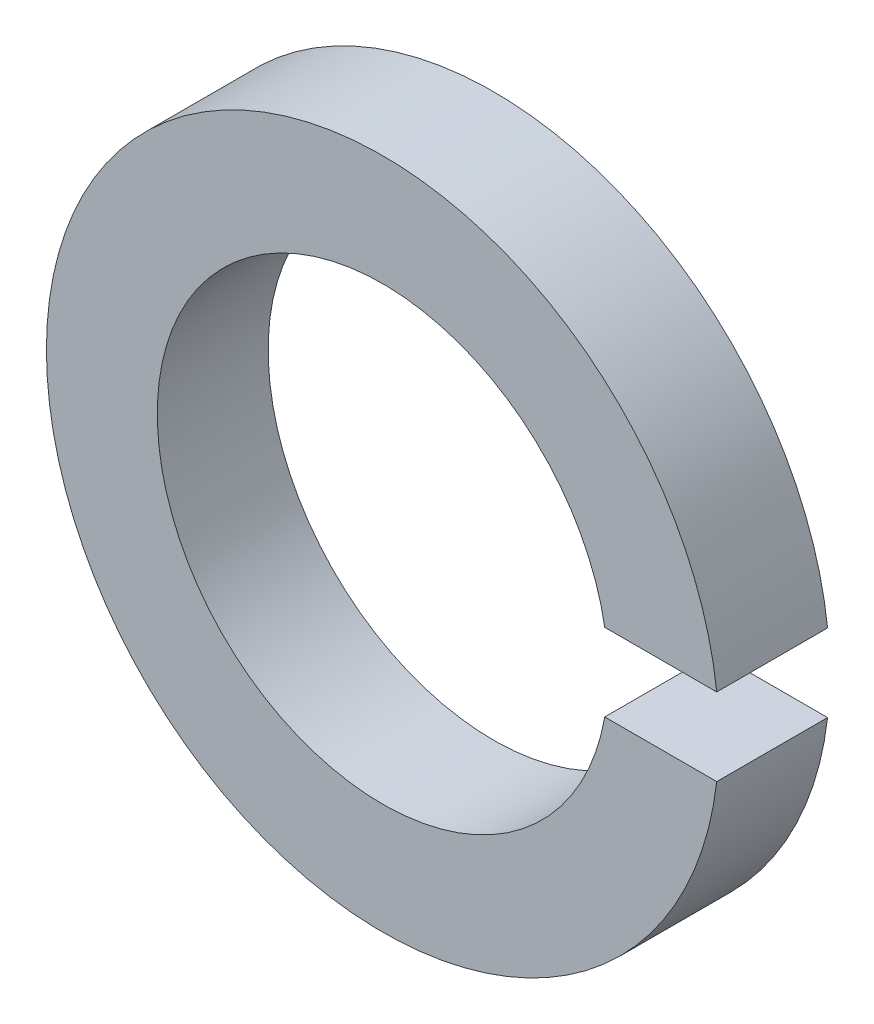
SolidWorks part; units mm, degrees
ref_plane "Спереди" through (0, 0, 0) normal (0, 0, 1) x (1, 0, 0)
ref_plane "Сверху" through (0, 0, 0) normal (0, 1, 0) x (1, 0, 0)
ref_plane "Справа" through (0, 0, 0) normal (1, 0, 0) x (0, 0, -1)
sketch "Эскиз1" plane through (0, 0, 0) normal (0, 0, 1) x (1, 0, 0)
  circle A0 centre (0, 0) radius 9.1
  circle A1 centre (0, 0) radius 6.1
  dimension "D1" = 18.2
  dimension "D2" = 12.2
extrude "Вытянуть1" add sketch "Эскиз1" along normal blind 3
sketch "Эскиз2" plane through (0, 0, 3) normal (0, 0, 1) x (1, 0, 0)
  line L0 (0, 0) -> (0.123, 0) construction
  line L1 (9.1, 0) -> (-9.1, 0) construction
  line L3 (5.8107, 1.05) -> (9.2803, 1.05)
  line L4 (5.8107, 1.05) -> (5.8107, -1.05)
  line L5 (5.8107, -1.05) -> (9.2803, -1.05)
  line L6 (9.2803, 1.05) -> (9.2803, -1.05)
  circle A0 centre (0, 0) radius 9.1 construction
  dimension "D1" = 1.05
  dimension "D2" = 2.1
extrude "Вырез-Вытянуть1" cut sketch "Эскиз2" against normal through all
